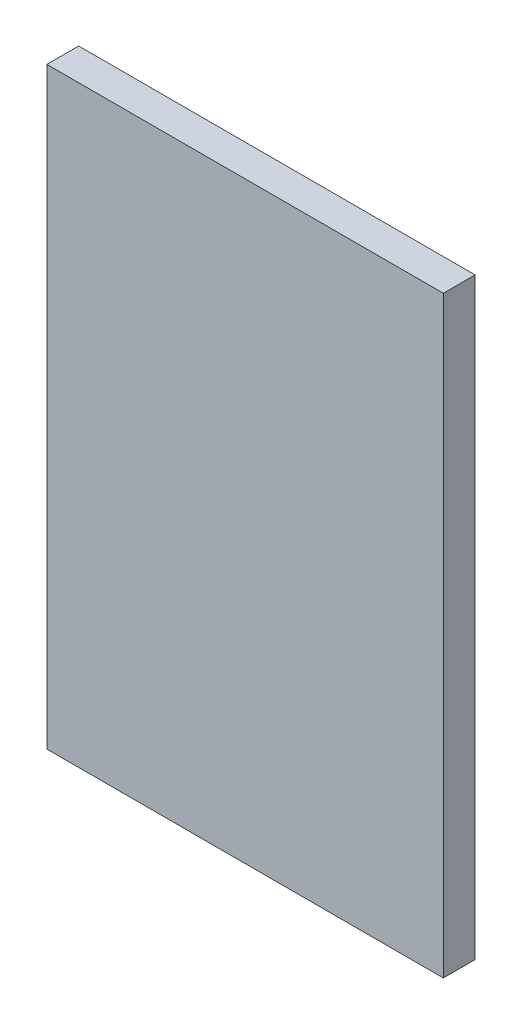
SolidWorks part; units mm, degrees
material "6061-T6 (SS)"
ref_plane "Front Plane" through (0, 0, 0) normal (0, 0, 1) x (1, 0, 0)
ref_plane "Top Plane" through (0, 0, 0) normal (0, 1, 0) x (1, 0, 0)
ref_plane "Right Plane" through (0, 0, 0) normal (1, 0, 0) x (0, 0, -1)
sketch "Sketch1" plane through (0, 0, 0) normal (0, 0, 1) x (1, 0, 0)
  line L1 (-87.25, 130.5) -> (87.25, 130.5)
  line L2 (-87.25, 130.5) -> (-87.25, -130.5)
  line L3 (-87.25, -130.5) -> (87.25, -130.5)
  line L4 (87.25, 130.5) -> (87.25, -130.5)
  line L5 (-87.25, 130.5) -> (87.25, -130.5) construction
  line L6 (-87.25, -130.5) -> (87.25, 130.5) construction
  point P0 (0, 0)
  dimension "D1" = 261
  dimension "D2" = 174.5
extrude "Boss-Extrude1" add sketch "Sketch1" along normal blind 14
